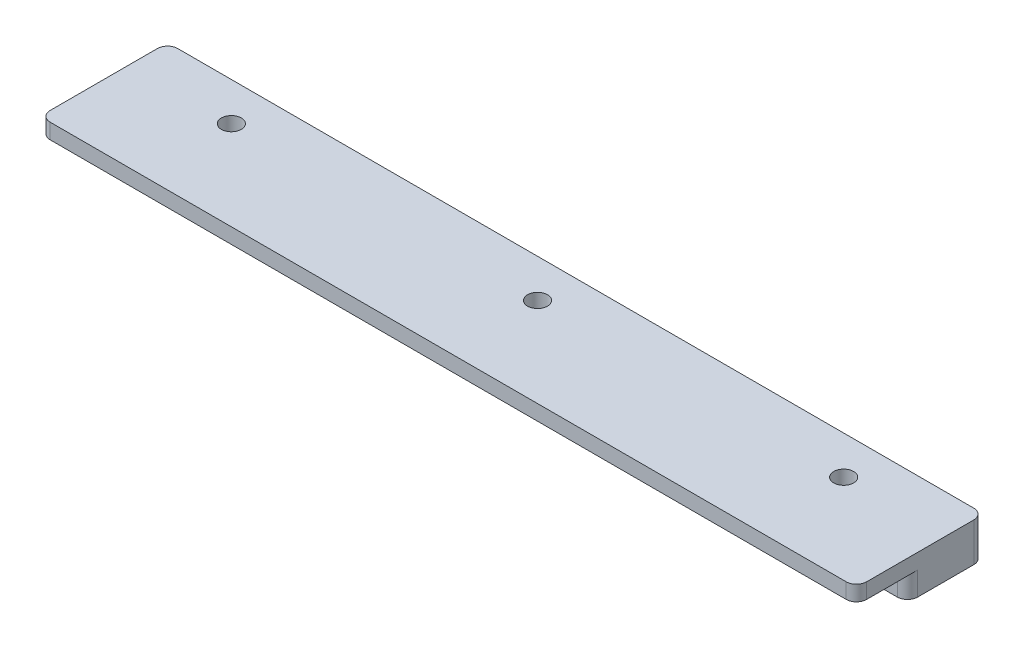
SolidWorks part; units mm, degrees
ref_plane "前视基准面" through (0, 0, 0) normal (0, 0, 1) x (1, 0, 0)
ref_plane "上视基准面" through (0, 0, 0) normal (0, 1, 0) x (1, 0, 0)
ref_plane "右视基准面" through (0, 0, 0) normal (1, 0, 0) x (0, 0, -1)
sketch "草图1" plane through (0, 0, 0) normal (1, 0, 0) x (0, 0, -1)
  line L0 (0, 0) -> (0, 7.6)
  line L1 (0, 7.6) -> (-25, 7.6)
  line L2 (-25, 7.6) -> (-25, 4.6)
  line L3 (-25, 4.6) -> (-15, 4.6)
  line L4 (-15, 4.6) -> (-15, 0)
  line L5 (-15, 0) -> (0, 0)
  dimension "D1" = 15
  dimension "D2" = 4.6
  dimension "D3" = 3
  dimension "D4" = 10
extrude "凸台-拉伸1" add sketch "草图1" along normal blind 160
sketch "草图2" plane through (0, 0, 0) normal (0, -1, 0) x (1, 0, 0)
  line L0 (0, 7.5) -> (160, 7.5) construction
  line L1 (0, 15) -> (0, 0) construction
  line L2 (160, 15) -> (160, 0) construction
  circle A0 centre (20, 7.5) radius 1.95
  circle A1 centre (140, 7.5) radius 1.95
  circle A2 centre (80, 7.5) radius 1.95
  point P10 (80, 7.5)
  dimension "D3" = 3.9
  dimension "D4" = 3.9
  dimension "D5" = 3.9
  dimension "D1" = 60
  dimension "D2" = 120
extrude "切除-拉伸1" cut sketch "草图2" against normal up to next
fillet "圆角1" radius 2 6 edges at (160, 6.1, 25) (160, 2.3, 15) (160, 3.8, 0) (0, 3.8, 0) (0, 2.3, 15) (0, 6.1, 25)
